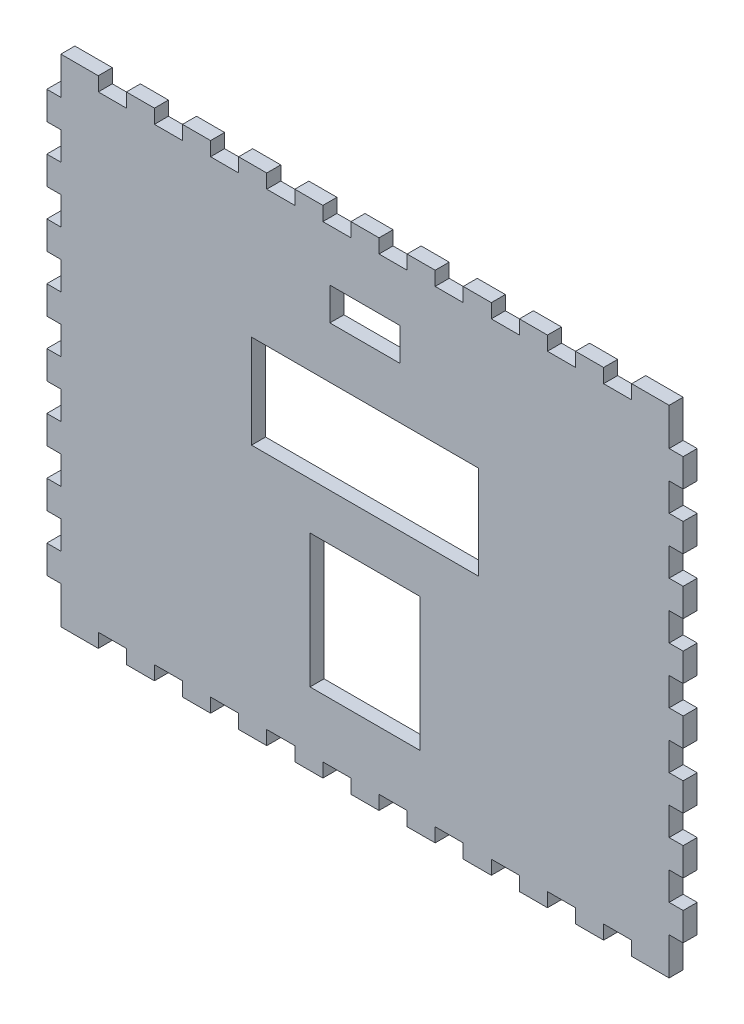
SolidWorks part; units mm, degrees
ref_plane "Front Plane" through (0, 0, 0) normal (0, 0, 1) x (1, 0, 0)
ref_plane "Top Plane" through (0, 0, 0) normal (0, 1, 0) x (1, 0, 0)
ref_plane "Right Plane" through (0, 0, 0) normal (1, 0, 0) x (0, 0, -1)
sketch "Model" plane through (0, 0, 0) normal (0, 0, 1) x (1, 0, 0)
  line L0 (221, 430) -> (221, 414)
  line L1 (221, 414) -> (215, 414)
  line L2 (215, 414) -> (215, 402)
  line L3 (215, 402) -> (221, 402)
  line L4 (221, 402) -> (221, 390)
  line L5 (221, 390) -> (215, 390)
  line L6 (215, 390) -> (215, 378)
  line L7 (215, 378) -> (221, 378)
  line L8 (221, 378) -> (221, 366)
  line L9 (221, 366) -> (215, 366)
  line L10 (215, 366) -> (215, 354)
  line L11 (215, 354) -> (221, 354)
  line L12 (221, 354) -> (221, 342)
  line L13 (221, 342) -> (215, 342)
  line L14 (215, 342) -> (215, 330)
  line L15 (215, 330) -> (221, 330)
  line L16 (221, 330) -> (221, 318)
  line L17 (221, 318) -> (215, 318)
  line L18 (215, 318) -> (215, 306)
  line L19 (215, 306) -> (221, 306)
  line L20 (221, 306) -> (221, 294)
  line L21 (221, 294) -> (215, 294)
  line L22 (215, 294) -> (215, 282)
  line L23 (215, 282) -> (221, 282)
  line L24 (221, 282) -> (221, 270)
  line L25 (221, 270) -> (215, 270)
  line L26 (215, 270) -> (215, 258)
  line L27 (215, 258) -> (221, 258)
  line L28 (221, 258) -> (221, 246)
  line L29 (221, 246) -> (215, 246)
  line L30 (215, 246) -> (215, 234)
  line L31 (215, 234) -> (221, 234)
  line L32 (221, 234) -> (221, 218)
  line L33 (221, 218) -> (237, 218)
  line L34 (237, 218) -> (237, 224)
  line L35 (237, 224) -> (249, 224)
  line L36 (249, 224) -> (249, 218)
  line L37 (249, 218) -> (261, 218)
  line L38 (261, 218) -> (261, 224)
  line L39 (261, 224) -> (273, 224)
  line L40 (273, 224) -> (273, 218)
  line L41 (273, 218) -> (285, 218)
  line L42 (285, 218) -> (285, 224)
  line L43 (285, 224) -> (297, 224)
  line L44 (297, 224) -> (297, 218)
  line L45 (297, 218) -> (309, 218)
  line L46 (309, 218) -> (309, 224)
  line L47 (309, 224) -> (321, 224)
  line L48 (321, 224) -> (321, 218)
  line L49 (321, 218) -> (333, 218)
  line L50 (333, 218) -> (333, 224)
  line L51 (333, 224) -> (345, 224)
  line L52 (345, 224) -> (345, 218)
  line L53 (345, 218) -> (357, 218)
  line L54 (357, 218) -> (357, 224)
  line L55 (357, 224) -> (369, 224)
  line L56 (369, 224) -> (369, 218)
  line L57 (369, 218) -> (381, 218)
  line L58 (381, 218) -> (381, 224)
  line L59 (381, 224) -> (393, 224)
  line L60 (393, 224) -> (393, 218)
  line L61 (393, 218) -> (405, 218)
  line L62 (405, 218) -> (405, 224)
  line L63 (405, 224) -> (417, 224)
  line L64 (417, 224) -> (417, 218)
  line L65 (417, 218) -> (429, 218)
  line L66 (429, 218) -> (429, 224)
  line L67 (429, 224) -> (441, 224)
  line L68 (441, 224) -> (441, 218)
  line L69 (441, 218) -> (453, 218)
  line L70 (453, 218) -> (453, 224)
  line L71 (453, 224) -> (465, 224)
  line L72 (465, 224) -> (465, 218)
  line L73 (465, 218) -> (477, 218)
  line L74 (477, 218) -> (481, 218)
  line L75 (481, 218) -> (481, 234)
  line L76 (481, 234) -> (487, 234)
  line L77 (487, 234) -> (487, 246)
  line L78 (487, 246) -> (481, 246)
  line L79 (481, 246) -> (481, 258)
  line L80 (481, 258) -> (487, 258)
  line L81 (487, 258) -> (487, 270)
  line L82 (487, 270) -> (481, 270)
  line L83 (481, 270) -> (481, 282)
  line L84 (481, 282) -> (487, 282)
  line L85 (487, 282) -> (487, 294)
  line L86 (487, 294) -> (481, 294)
  line L87 (481, 294) -> (481, 306)
  line L88 (481, 306) -> (487, 306)
  line L89 (487, 306) -> (487, 318)
  line L90 (487, 318) -> (481, 318)
  line L91 (481, 318) -> (481, 330)
  line L92 (481, 330) -> (487, 330)
  line L93 (487, 330) -> (487, 342)
  line L94 (487, 342) -> (481, 342)
  line L95 (481, 342) -> (481, 354)
  line L96 (481, 354) -> (487, 354)
  line L97 (487, 354) -> (487, 366)
  line L98 (487, 366) -> (481, 366)
  line L99 (481, 366) -> (481, 378)
  line L100 (481, 378) -> (487, 378)
  line L101 (487, 378) -> (487, 390)
  line L102 (487, 390) -> (481, 390)
  line L103 (481, 390) -> (481, 402)
  line L104 (481, 402) -> (487, 402)
  line L105 (487, 402) -> (487, 414)
  line L106 (487, 414) -> (481, 414)
  line L107 (481, 414) -> (481, 430)
  line L108 (481, 430) -> (465, 430)
  line L109 (465, 430) -> (465, 424)
  line L110 (465, 424) -> (453, 424)
  line L111 (453, 424) -> (453, 430)
  line L112 (453, 430) -> (441, 430)
  line L113 (441, 430) -> (441, 424)
  line L114 (441, 424) -> (429, 424)
  line L115 (429, 424) -> (429, 430)
  line L116 (429, 430) -> (417, 430)
  line L117 (417, 430) -> (417, 424)
  line L118 (417, 424) -> (405, 424)
  line L119 (405, 424) -> (405, 430)
  line L120 (405, 430) -> (393, 430)
  line L121 (393, 430) -> (393, 424)
  line L122 (393, 424) -> (381, 424)
  line L123 (381, 424) -> (381, 430)
  line L124 (381, 430) -> (369, 430)
  line L125 (369, 430) -> (369, 424)
  line L126 (369, 424) -> (357, 424)
  line L127 (357, 424) -> (357, 430)
  line L128 (357, 430) -> (345, 430)
  line L129 (345, 430) -> (345, 424)
  line L130 (345, 424) -> (333, 424)
  line L131 (333, 424) -> (333, 430)
  line L132 (333, 430) -> (321, 430)
  line L133 (321, 430) -> (321, 424)
  line L134 (321, 424) -> (309, 424)
  line L135 (309, 424) -> (309, 430)
  line L136 (309, 430) -> (297, 430)
  line L137 (297, 430) -> (297, 424)
  line L138 (297, 424) -> (285, 424)
  line L139 (285, 424) -> (285, 430)
  line L140 (285, 430) -> (273, 430)
  line L141 (273, 430) -> (273, 424)
  line L142 (273, 424) -> (261, 424)
  line L143 (261, 424) -> (261, 430)
  line L144 (261, 430) -> (249, 430)
  line L145 (249, 430) -> (249, 424)
  line L146 (249, 424) -> (237, 424)
  line L147 (237, 424) -> (237, 430)
  line L148 (237, 430) -> (225, 430)
  line L149 (225, 430) -> (221, 430)
extrude "Boss-Extrude1" add sketch "Model" along normal blind 6
sketch "Sketch2" plane through (0, 0, 6) normal (0, 0, 1) x (1, 0, 0)
  line L0 (215, 264) -> (327.5, 264)
  line L1 (302.5, 366) -> (399.5, 366)
  line L2 (302.5, 366) -> (302.5, 326)
  line L3 (302.5, 326) -> (399.5, 326)
  line L4 (399.5, 366) -> (399.5, 326)
  line L5 (336, 402) -> (366, 402)
  line L6 (336, 402) -> (336, 388)
  line L7 (336, 388) -> (366, 388)
  line L8 (366, 402) -> (366, 388)
  line L9 (327.5, 306) -> (374.5, 306)
  line L10 (327.5, 306) -> (327.5, 249)
  line L11 (327.5, 249) -> (374.5, 249)
  line L12 (374.5, 306) -> (374.5, 249)
  line L13 (215, 270) -> (215, 258) construction
  line L14 (487, 264) -> (374.5, 264)
  line L15 (487, 258) -> (487, 270) construction
  line L16 (366, 395) -> (487, 395)
  line L17 (487, 378) -> (487, 390) construction
  line L18 (336, 395) -> (215, 395)
  line L19 (215, 390) -> (215, 378) construction
  line L20 (399.5, 346) -> (487, 346)
  line L21 (487, 330) -> (487, 342) construction
  line L22 (302.5, 346) -> (215, 346)
  line L23 (215, 342) -> (215, 330) construction
  line L24 (357, 224) -> (369, 224) construction
  dimension "D1" = 40
  dimension "D2" = 97
  dimension "D3" = 14
  dimension "D4" = 30
  dimension "D5" = 25
  dimension "D6" = 22
  dimension "D7" = 47
  dimension "D8" = 57
  dimension "D9" = 20
extrude "Cut-Extrude1" cut sketch "Sketch2" against normal blind 6 contours L8 L5 L6 L7 | L4 L1 L2 L3 | L12 L9 L10 L11
